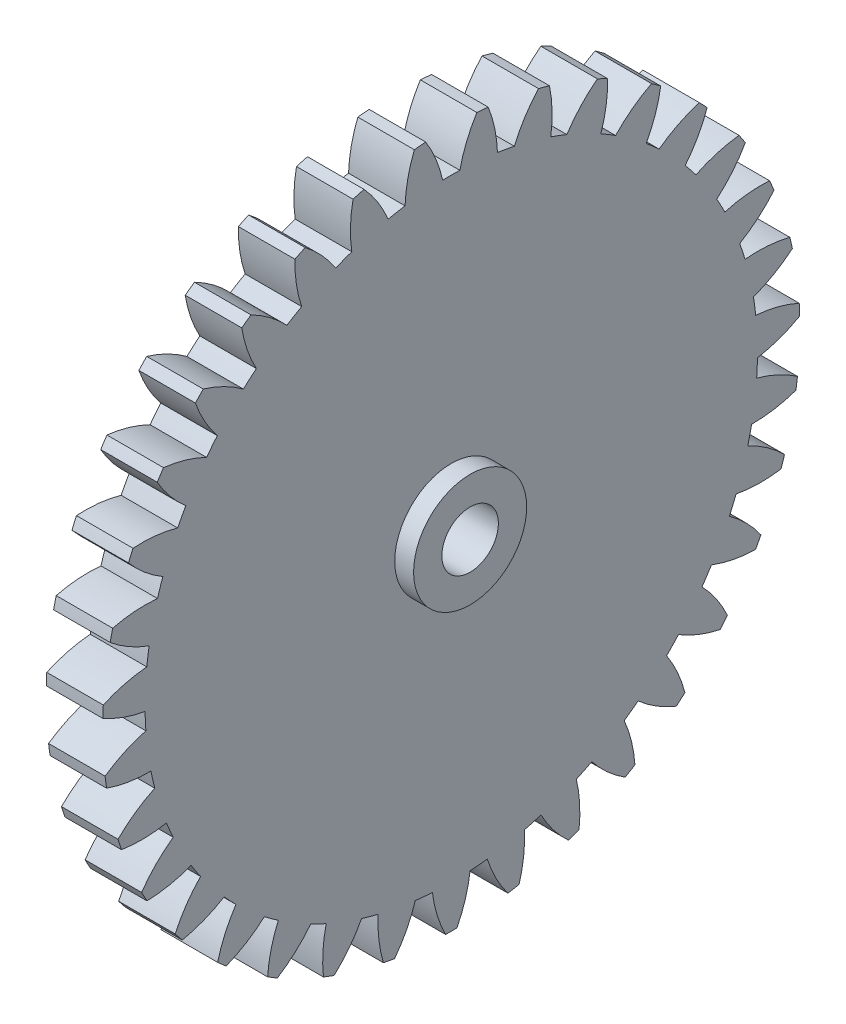
SolidWorks part; units mm, degrees
ref_plane "Plane1" through (0, 0, 0) normal (0, 0, 1) x (1, 0, 0)
ref_plane "Plane2" through (0, 0, 0) normal (0, 1, 0) x (1, 0, 0)
ref_plane "Plane3" through (0, 0, 0) normal (1, 0, 0) x (0, 0, -1)
sketch "HoldingSke" plane through (0, 0, 0) normal (0, 1, 0) x (1, 0, 0)
  line L0 (0, 0) -> (0.8192, -0.5736)
  line L1 (-15, 0) -> (100, 0) construction
  line L2 (0, 0) -> (-2.1039, 2.3779)
  line L3 (0, 0) -> (-11.863, 4.5341)
  line L4 (0, 0) -> (7.0742, 4.9534)
  line L5 (0, 0) -> (-4.6848, -1.7473)
  line L6 (0, 0) -> (-2.4869, -1.6779)
  line L7 (-2.1039, 2.3779) -> (-1.0276, 7.2607)
  line L8 (-76.2, 54.61) -> (-75.7, 54.61)
  line L9 (-71.009, 38.7566) -> (-53.1078, 45.2721)
  line L10 (-76.2, 71.12) -> (104.1128, 71.12)
  line L11 (0, 0) -> (-3, 0)
  line L12 (-76.2, 101.6) -> (-76.162, 101.6)
  line L13 (24.9733, 27.94) -> (52.9518, 28.4284)
  line L14 (24.9733, 27.94) -> (24.9743, 27.94)
  line L15 (24.9733, 27.94) -> (100.4006, 29.5858)
  line L16 (-63.627, -1) -> (-12.827, -1)
  circle A0 centre (0, 0) radius 1.5
  circle A1 centre (0, 0) radius 3
  circle A2 centre (0, 0) radius 3
  circle A3 centre (0, 0) radius 1.5
  dimension "MHD" = 6
  dimension "Hub_dia" = 6
  dimension "Bore" = 3
  dimension "MBD" = 3
  dimension "Pitch" = 1
  dimension "T_dim" = 0.5
  dimension "H" = 19.05
  dimension "Pitch_radius" = 180.3128
  dimension "Backlash" = 0.038
  dimension "Addendum_fac" = 1
  dimension "Dedendum_fac" = 1.25
  dimension "Clearance_fac" = 0.25
  dimension "Dedendum_add" = 0.001
  dimension "Module" = 1
sketch "BasProSke" plane through (0, 0, 0) normal (0, 1, 0) x (1, 0, 0)
  line L0 (-10, 0) -> (60, 0) construction
  line L1 (0, 0) -> (0, 18.5)
  line L2 (0, 0) -> (3, 0)
  line L3 (3, 0) -> (3, 18.5)
  line L4 (3, 18.5) -> (0, 18.5)
revolve "Base-Revolve" add sketch "BasProSke" angle 360 about L0
sketch "TooCutSke" plane through (0, 0, 0) normal (1, 0, 0) x (0, 0, -1)
  line L1 (0, 0) -> (0, 107) construction
  line L2 (0, 0) -> (-0.8516, 17.4793) construction
  line L3 (0, 0) -> (-3.1347, 34.8297) construction
  line L4 (-0.8516, 17.4793) -> (-1.5674, 17.4148) construction
  arc A0 (0.4564, 16.2426) -> (-0.4564, 16.2426) centre (0, 0) ccw
  arc A1 (1.373, 18.4745) -> (-1.373, 18.4745) centre (0, 0) ccw
  circle A2 centre (0, 0) radius 17.5 construction
  circle A3 centre (0, 0) radius 16.4446 construction
  arc A4 (-0.4564, 16.2426) -> (-1.373, 18.4745) centre (-7.293, 14.739) ccw
  arc A5 (1.373, 18.4745) -> (0.4564, 16.2426) centre (7.293, 14.739) ccw
extrude "ToothCut" cut sketch "TooCutSke" along normal through all
fillet "Breaks" [suppressed] radius 0.02
fillet "RootFillets" [suppressed] radius 0.251
pattern_circular "TeethCuts" count 35 every 10.286 about axis through (-10, 0, 0) along (1, 0, 0) of "ToothCut", "RootFillets", "Breaks"
sketch "HubNeaOneSke" plane through (0, 0, 0) normal (-1, 0, 0) x (0, 0, 1)
  circle A0 centre (0, 0) radius 3
  dimension "Diameter" = 6
extrude "HubNearOne" [suppressed] add sketch "HubNeaOneSke" along normal blind 2.0001
sketch "HubNeaBotSke" plane through (0, 0, 0) normal (-1, 0, 0) x (0, 0, 1)
  circle A0 centre (0, 0) radius 3
  dimension "Diameter" = 6
extrude "HubNearBoth" add sketch "HubNeaBotSke" along normal blind 1
ref_plane "FarPln" through (3, 0, 0) normal (1, 0, 0) x (0, 0, -1)
sketch "HubFarSke" plane through (3, 0, 0) normal (1, 0, 0) x (0, 0, -1)
  circle A0 centre (0, 0) radius 3
  dimension "Diameter" = 6
extrude "HubFar" add sketch "HubFarSke" along normal blind 1
sketch "BorSke" plane through (0, 0, 0) normal (1, 0, 0) x (0, 0, -1)
  circle A0 centre (0, 0) radius 1.5
  dimension "Diameter" = 3
extrude "Bore" cut sketch "BorSke" along normal mid plane 10.0001
sketch "KeySke" plane through (0, 0, 0) normal (1, 0, 0) x (0, 0, -1)
  line L0 (-0.6, 0) -> (-0.6, 2)
  line L1 (-0.6, 2) -> (0.6, 2)
  line L2 (0.6, 2) -> (0.6, 0)
  line L3 (0, 0) -> (0, 34) construction
  line L4 (-0.6, 0) -> (0.6, 0)
  dimension "Offset" = 2
  dimension "Width" = 1.2
extrude "Keyway" [suppressed] cut sketch "KeySke" along normal mid plane 10.0001
pattern_circular "Keyway2" [suppressed] count 2 every 90 about axis through (-10, 0, 0) along (1, 0, 0)
equation "' \"Module@HoldingSke\" = 6.35"
equation "' \"Num_teeth@HoldingSke\" = 12"
equation "' \"Ap@HoldingSke\" =  20"
equation "' \"Ap@HoldingSke\" = 20"
equation "' \"Width@HoldingSke\" = 0.5 * 25.4"
equation "' \"Hub_dia@HoldingSke\"= 1 * 25.4"
equation "' \"Hub_dia@HoldingSke\" = 1 * 25.4"
equation "' \"Overall_len@HoldingSke\" = 1.0 * 25.4"
equation "' \"Bore@HoldingSke\" = 0.75 * 25.4"
equation "' \"T_dim@HoldingSke\" = 0.1 * 25.4"
equation "' \"Width@KeySke\" = 0.25 * 25.4"
equation "' \"Show_teeth@HoldingSke\" = 13"
equation "' \"Backlash@HoldingSke\" = 0.009 * 25.4"
equation "' \"Addendum_fac@HoldingSke\" = 1.0"
equation "' \"Dedendum_fac@HoldingSke\" = 1.25"
equation "' \"Dedendum_add@HoldingSke\" = 0.00005 * 25.4"
equation "' \"Clearance_fac@HoldingSke\" = 0.25"
equation "\"Pitch@HoldingSke\" = 1 / \"Module@HoldingSke\""
equation "\"Overcut_dia@TooCutSke\" = (\"Num_teeth@HoldingSke\" + 2 * \"Addendum_fac@HoldingSke\") / \"Pitch@HoldingSke\" + 0.002 * 25.4"
equation "\"Pitch_dia@TooCutSke\" = \"Num_teeth@HoldingSke\" / \"Pitch@HoldingSke\""
equation "\"Base_dia@TooCutSke\" = \"Num_teeth@HoldingSke\" / \"Pitch@HoldingSke\" * cos((\"Ap@HoldingSke\"  * 3.14159265 / 180))"
equation "\"Root_dia@TooCutSke\" = (\"Num_teeth@HoldingSke\" + 2) / \"Pitch@HoldingSke\" - 2 * (\"Addendum_fac@HoldingSke\" + \"Dedendum_fac@HoldingSke\") / \"Pitch@HoldingSke\" - \"Dedendum_add@HoldingSke\" * 2"
equation "\"Half_ang@TooCutSke\" = 180 / \"Num_teeth@HoldingSke\""
equation "\"Half_CT@TooCutSke\" = \"Num_teeth@HoldingSke\" / \"Pitch@HoldingSke\" * sin((3.14159265 / 2 / \"Num_teeth@HoldingSke\")) / 2 - 7 * \"Backlash@HoldingSke\" / 4"
equation "\"Flank_rad@TooCutSke\" = \"Num_teeth@HoldingSke\" / \"Pitch@HoldingSke\" / 5"
equation "\"Radius@RootFillets\" = \"Clearance_fac@HoldingSke\" / \"Pitch@HoldingSke\" + \"Dedendum_add@HoldingSke\""
equation "\"Break_rad@Breaks\" = 0.02 / \"Pitch@HoldingSke\""
equation "\"Thickness@HoldingSke\" = \"Width@HoldingSke\""
equation "\"OAL@HoldingSke\" = \"Thickness@HoldingSke\""
equation "\"MHD@HoldingSke\" = (\"Num_teeth@HoldingSke\" + 2) / \"Pitch@HoldingSke\" - 2 * (\"Addendum_fac@HoldingSke\" + \"Dedendum_fac@HoldingSke\")  / \"Pitch@HoldingSke\" - \"Dedendum_add@HoldingSke\" * 2"
equation "\"MBD@HoldingSke\" = (\"Num_teeth@HoldingSke\" + 2) / \"Pitch@HoldingSke\" - 2 * (\"Addendum_fac@HoldingSke\" + \"Dedendum_fac@HoldingSke\")  / \"Pitch@HoldingSke\" - \"Dedendum_add@HoldingSke\" * 2 - 0.002 * 25.4"
equation "\"MHD@HoldingSke\" = ((sgn( \"MHD@HoldingSke\" - \"Hub_dia@HoldingSke\" )-1)*( \"MHD@HoldingSke\" - \"Hub_dia@HoldingSke\" ))/-2+ \"Hub_dia@HoldingSke\""
equation "\"MBD@HoldingSke\" = ((sgn( \"MBD@HoldingSke\" - \"Bore@HoldingSke\" )-1)*( \"MBD@HoldingSke\" - \"Bore@HoldingSke\" ))/-2+ \"Bore@HoldingSke\""
equation "\"OAL@HoldingSke\" = ((sgn( \"OAL@HoldingSke\" - \"Overall_len@HoldingSke\" )+1)*( \"OAL@HoldingSke\" - \"Overall_len@HoldingSke\" ))/2 + \"Overall_len@HoldingSke\" + 0.000002 * 25.4"
equation "\"Num_teeth@TeethCuts\" = int( \"Show_teeth@HoldingSke\" ) + 1"
equation "\"Num_teeth@TeethCuts\" = ((sgn( \"Num_teeth@TeethCuts\" - \"Num_teeth@HoldingSke\" )-1)*( \"Num_teeth@TeethCuts\" - \"Num_teeth@HoldingSke\" ))/-2+ \"Num_teeth@HoldingSke\""
equation "\"Num_teeth@TeethCuts\" = ((sgn( \"Num_teeth@TeethCuts\" - 2.0)+1)*( \"Num_teeth@TeethCuts\" - 2.0))/2 +2.0"
equation "\"Angle@TeethCuts\" = 360.0 / \"Num_teeth@HoldingSke\""
equation "\"Diameter@BasProSke\" = (\"Num_teeth@HoldingSke\" + 2 * \"Addendum_fac@HoldingSke\") / \"Pitch@HoldingSke\""
equation "\"Thickness@BasProSke\"  = \"Thickness@HoldingSke\""
equation "' \"Fillet_rad@BasProSke\" =  \"Thickness@HoldingSke\" * 0.05"
equation "' \"Fillet_rad@BasProSke\" = \"Thickness@HoldingSke\" * 0.05"
equation "\"MHD@HoldingSke\" = ((sgn( \"MHD@HoldingSke\" - \"Root_dia@TooCutSke\" )-1)*( \"MHD@HoldingSke\" - \"Root_dia@TooCutSke\" ))/-2+ \"Root_dia@TooCutSke\""
equation "\"Diameter@HubNeaOneSke\" = \"MHD@HoldingSke\""
equation "\"Length@HubNearOne\" = \"OAL@HoldingSke\" - \"Thickness@BasProSke\""
equation "\"Diameter@HubNeaBotSke\" = \"MHD@HoldingSke\""
equation "\"Length@HubNearBoth\" = ( \"OAL@HoldingSke\" - \"Thickness@BasProSke\" ) / 2.0"
equation "\"Thickness@FarPln\" = \"Thickness@BasProSke\""
equation "\"Diameter@HubFarSke\" = \"MHD@HoldingSke\""
equation "\"Length@HubFar\" = ( \"OAL@HoldingSke\" - \"Thickness@BasProSke\" ) / 2.0"
equation "\"Diameter@BorSke\" = \"MBD@HoldingSke\""
equation "\"D1@Bore\" = \"OAL@HoldingSke\" * 2.0"
equation "\"D1@Keyway\" = \"OAL@HoldingSke\" * 2.0"
equation "\"Offset@KeySke\" = \"T_dim@HoldingSke\" + \"MBD@HoldingSke\" / 2.0"
